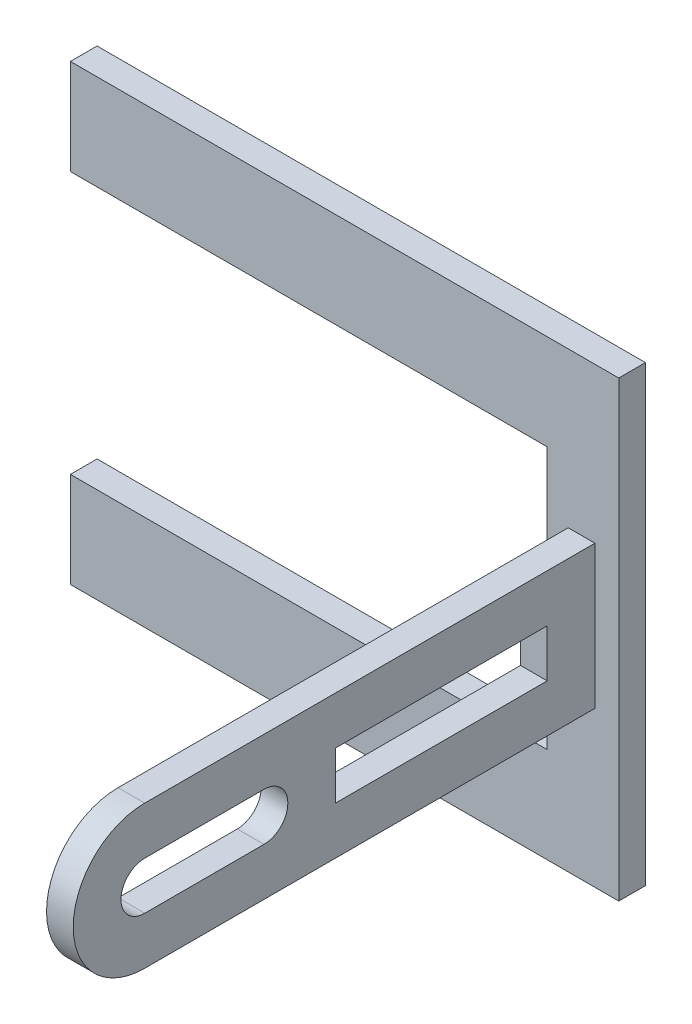
SolidWorks part; units mm, degrees
ref_plane "Front Plane" through (0, 0, 0) normal (0, 0, 1) x (1, 0, 0)
ref_plane "Top Plane" through (0, 0, 0) normal (0, 1, 0) x (1, 0, 0)
ref_plane "Right Plane" through (0, 0, 0) normal (1, 0, 0) x (0, 0, -1)
sketch "Sketch1" plane through (0, 0, 0) normal (0, 0, 1) x (1, 0, 0)
  line L0 (-25, -13.75) -> (25, -13.75)
  line L1 (25, -13.75) -> (25, 13.75)
  line L2 (25, 13.75) -> (-25, 13.75)
  line L3 (-25, 13.75) -> (-25, 23.75)
  line L4 (-25, 23.75) -> (32.5, 23.75)
  line L5 (32.5, 23.75) -> (32.5, -23.75)
  line L6 (32.5, -23.75) -> (-25, -23.75)
  line L7 (-25, -23.75) -> (-25, -13.75)
  point P3 (25, 0)
  dimension "D1" = 10
  dimension "D2" = 10
  dimension "D3" = 25
  dimension "D4" = 7.5
  dimension "D5" = 27.5
  dimension "D6" = 25
extrude "Boss-Extrude1" add sketch "Sketch1" along normal blind 2.8
ref_plane "Plane1" through (30, 0, 0) normal (1, 0, 0) x (0, 0, -1)
sketch "Sketch2" plane through (30, 0, 0) normal (1, 0, 0) x (0, 0, -1)
  line L0 (-2.8, -23.75) -> (-2.8, 23.75) construction
  line L1 (-2.8, -7.5) -> (-2.8, 7.5)
  line L2 (-2.8, 7.5) -> (-50, 7.5)
  line L4 (-50, -7.5) -> (-2.8, -7.5)
  line L5 (-50, -2.5) -> (-37.5, -2.5)
  line L6 (-7.8, -2.5) -> (-7.8, 2.5)
  line L7 (-7.8, 2.5) -> (-30, 2.5)
  line L8 (-30, 2.5) -> (-30, -2.5)
  line L10 (-37.5, 2.5) -> (-50, 2.5)
  line L11 (-30, -2.5) -> (-7.8, -2.5)
  line L12 (-7.8, 2.5) -> (-50, 2.5) construction
  line L14 (-50, -2.5) -> (-7.8, -2.5) construction
  arc A0 (-50, 7.5) -> (-50, -7.5) centre (-50, 0) ccw
  arc A1 (-50, 2.5) -> (-50, -2.5) centre (-50, 0) ccw
  arc A2 (-37.5, 2.5) -> (-37.5, -2.5) centre (-37.5, 0) cw
  point P13 (-2.8, 0)
  dimension "D2" = 7.5
  dimension "D3" = 50
  dimension "D4" = 12.5
  dimension "D5" = 7.5
  dimension "D1" = 5
extrude "Boss-Extrude2" add sketch "Sketch2" against normal blind 2.8
